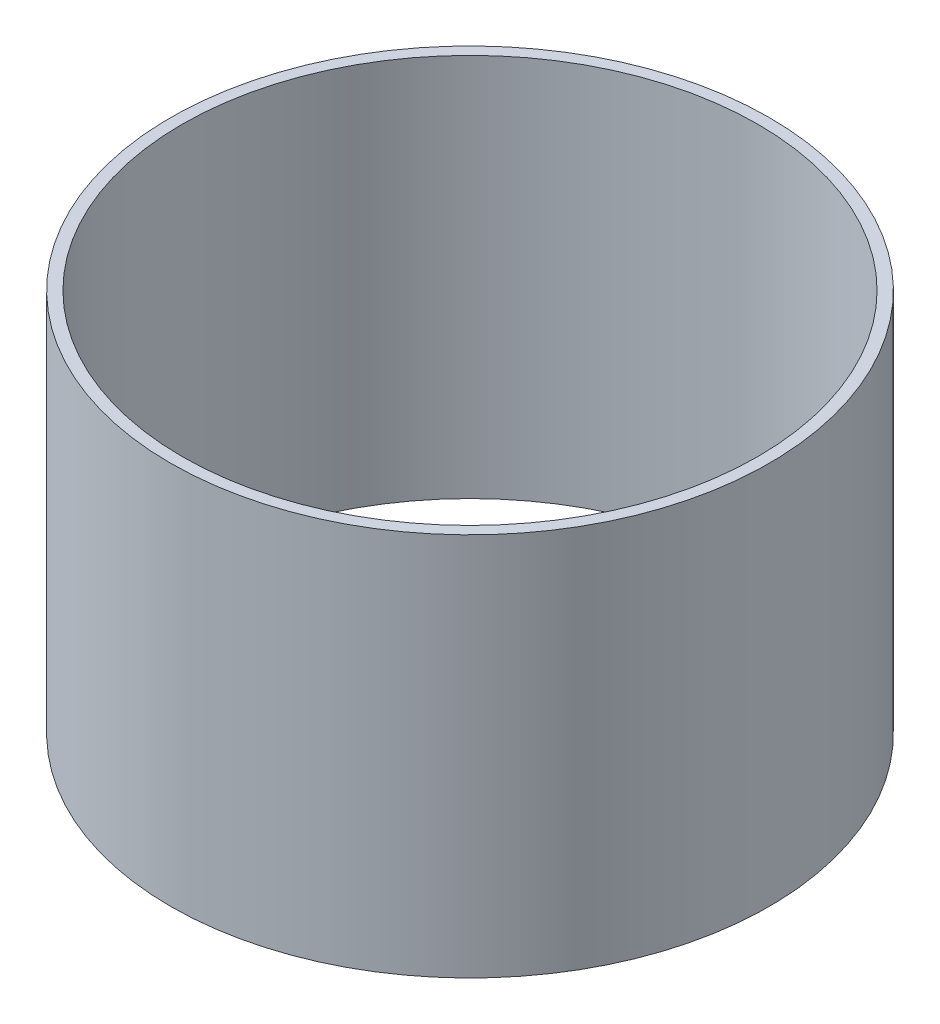
SolidWorks part; units mm, degrees
ref_plane "Front Plane" through (0, 0, 0) normal (0, 0, 1) x (1, 0, 0)
ref_plane "Top Plane" through (0, 0, 0) normal (0, 1, 0) x (1, 0, 0)
ref_plane "Right Plane" through (0, 0, 0) normal (1, 0, 0) x (0, 0, -1)
sketch "Sketch1" plane through (0, 0, 0) normal (0, 1, 0) x (1, 0, 0)
  circle A0 centre (0, 0) radius 39.624
  circle A1 centre (0, 0) radius 38.1
  dimension "D1" = 79.248
  dimension "D2" = 76.2
extrude "Boss-Extrude1" add sketch "Sketch1" along normal blind 50.8
